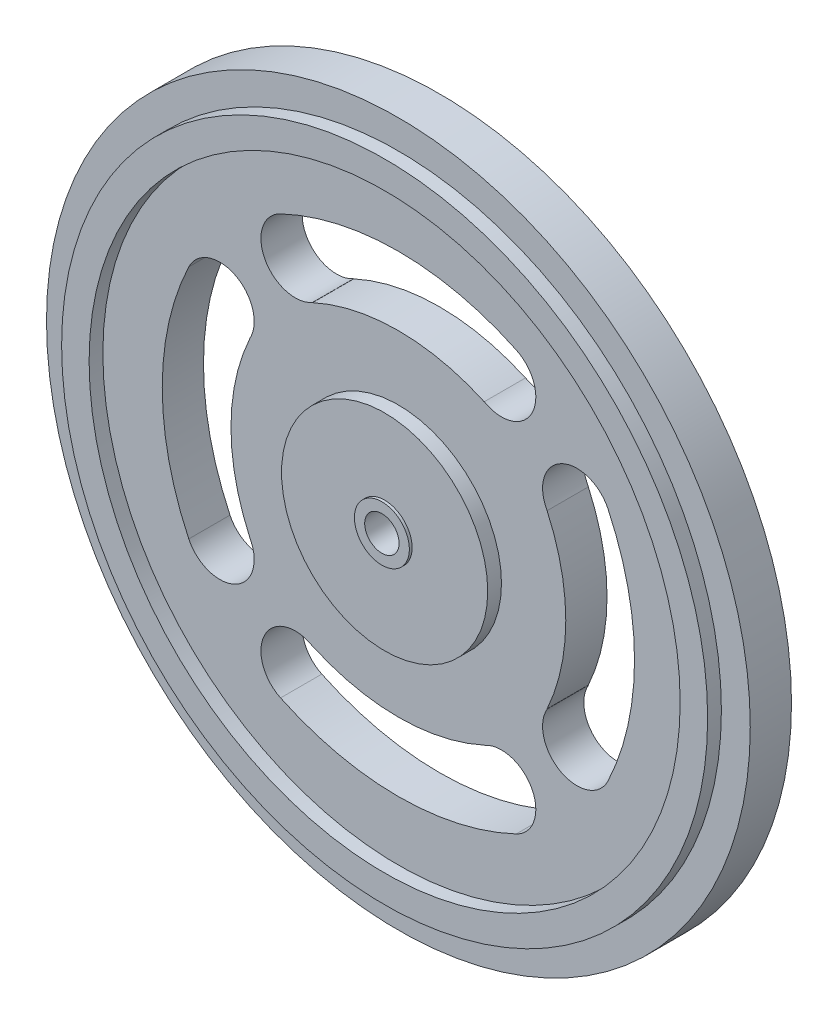
SolidWorks part; units mm, degrees
material "ABS"
ref_plane "Front Plane" through (0, 0, 0) normal (0, 0, 1) x (1, 0, 0)
ref_plane "Top Plane" through (0, 0, 0) normal (0, 1, 0) x (1, 0, 0)
ref_plane "Right Plane" through (0, 0, 0) normal (1, 0, 0) x (0, 0, -1)
sketch "Sketch1" plane through (0, 0, 0) normal (0, 0, 1) x (1, 0, 0)
  circle A0 centre (0, 0) radius 32.512
  dimension "D1" = 65.024
extrude "Boss-Extrude1" add sketch "Sketch1" along normal mid plane 3.81
sketch "Sketch2" plane through (0, 0, 1.905) normal (0, 0, 1) x (1, 0, 0)
  circle A0 centre (0, 0) radius 29.845
  circle A1 centre (0, 0) radius 27.305
  dimension "D1" = 59.69
  dimension "D2" = 2.54
extrude "Boss-Extrude2" add sketch "Sketch2" along normal blind 1.27 contours A0 | A1
sketch "Sketch3" plane through (0, 0, 1.905) normal (0, 0, 1) x (1, 0, 0)
  circle A0 centre (0, 0) radius 9.525
  dimension "D1" = 19.05
extrude "Boss-Extrude3" add sketch "Sketch3" along normal blind 1.27
sketch "Sketch4" plane through (0, 0, 1.905) normal (0, 0, 1) x (1, 0, 0)
  line L0 (0, 0) -> (0, 27.305) construction
  line L1 (-9.525, 16.4978) -> (0, 0)
  line L2 (0, 0) -> (9.525, 16.4978)
  circle A0 centre (0, 0) radius 27.305 construction
  circle A1 centre (0, 0) radius 27.305 construction
  arc A2 (9.525, 16.4978) -> (-9.525, 16.4978) centre (0, -4.2833) ccw construction
  circle A3 centre (-9.525, 16.4978) radius 3.175
  circle A4 centre (9.525, 16.4978) radius 3.175
  arc A5 (10.8857, 19.3664) -> (-10.8857, 19.3664) centre (0, -3.5827) ccw
  arc A6 (-8.1643, 13.6291) -> (8.1643, 13.6291) centre (0, -3.5827) cw
  dimension "D1" = 30
  dimension "D3" = 22.86
  dimension "D5" = 6.35
  dimension "D6" = 25.4
  dimension "D7" = 19.05
  dimension "D2" = 30
  dimension "D4" = 19.05
extrude "Cut-Extrude1" cut sketch "Sketch4" against normal up to next
pattern_circular "CirPattern1" count 4 over 360 about axis through (0, 0, 0) along (0, 0, 1) of "Cut-Extrude1"
sketch "Sketch5" plane through (0, 0, 3.175) normal (0, 0, 1) x (1, 0, 0)
  circle A0 centre (0, 0) radius 2.54
  circle A1 centre (0, 0) radius 1.5875
  dimension "D1" = 3.175
  dimension "D2" = 5.08
extrude "Boss-Extrude4" add sketch "Sketch5" along normal blind 0.254
mirror "Mirror1" about plane through (0, 0, 0) normal (0, 0, 1) of "Boss-Extrude2", "Boss-Extrude4", "Boss-Extrude3"
sketch "Sketch6" plane through (0, 0, 3.175) normal (0, 0, 1) x (1, 0, 0)
  circle A0 centre (0, 0) radius 1.5875
extrude "Cut-Extrude2" cut sketch "Sketch6" against normal up to next
